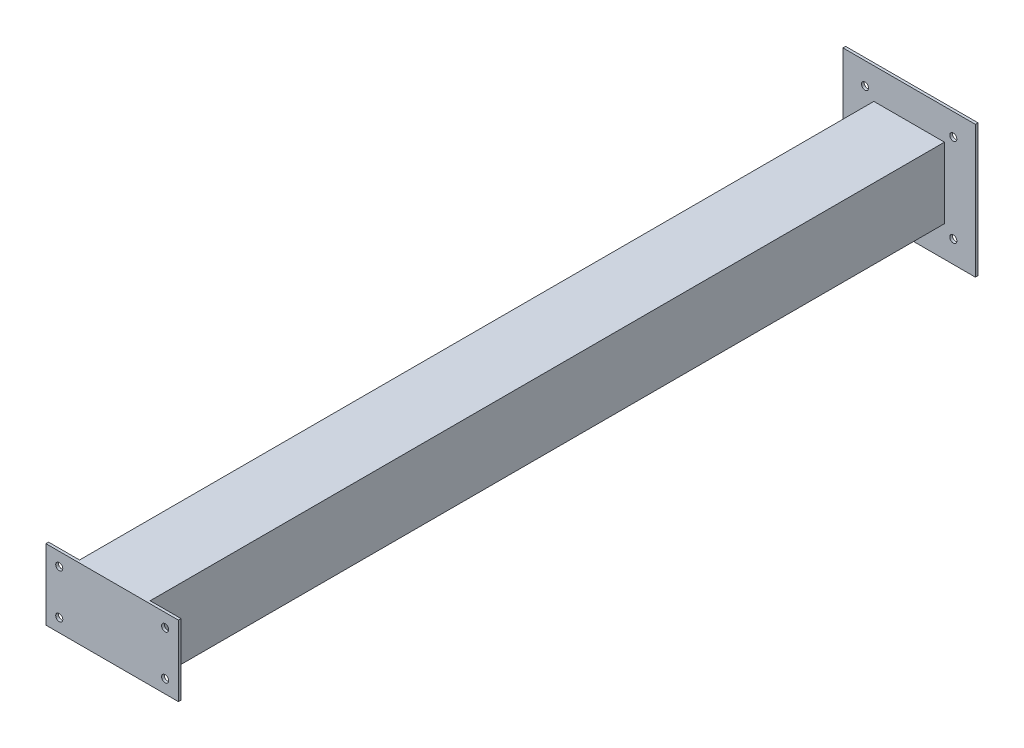
SolidWorks part; units mm, degrees
ref_plane "Front Plane" through (0, 0, 0) normal (0, 0, 1) x (1, 0, 0)
ref_plane "Top Plane" through (0, 0, 0) normal (0, 1, 0) x (1, 0, 0)
ref_plane "Right Plane" through (0, 0, 0) normal (1, 0, 0) x (0, 0, -1)
sketch "Sketch1" plane through (0, 0, 0) normal (0, 0, 1) x (1, 0, 0)
  line L1 (-40, 40) -> (40, 40)
  line L2 (-40, 40) -> (-40, -40)
  line L3 (-40, -40) -> (40, -40)
  line L4 (40, 40) -> (40, -40)
  line L5 (-40, 40) -> (40, -40) construction
  line L6 (-40, -40) -> (40, 40) construction
  point P0 (0, 0)
  dimension "D1" = 80
  dimension "D2" = 80
extrude "Boss-Extrude1" add sketch "Sketch1" along normal blind 900
shell "Shell1" thickness 3
sketch "Sketch2" plane through (0, 0, 0) normal (0, 0, -1) x (-1, 0, 0)
  line L0 (0, 75) -> (0, -75) construction
  line L1 (75, -75) -> (-75, -75)
  line L2 (75, -75) -> (75, 75)
  line L3 (75, 75) -> (-75, 75)
  line L4 (-75, -75) -> (-75, 75)
  line L5 (75, -75) -> (-75, 75) construction
  line L6 (75, 75) -> (-75, -75) construction
  line L7 (-75, 0) -> (75, 0) construction
  circle A0 centre (50, 50) radius 4
  circle A1 centre (-50, 50) radius 4
  circle A2 centre (50, -50) radius 4
  circle A3 centre (-50, -50) radius 4
  point P0 (0, 0)
  dimension "D5" = 8
  dimension "D1" = 100
  dimension "D2" = 100
  dimension "D3" = 150
  dimension "D4" = 150
extrude "Boss-Extrude2" add sketch "Sketch2" along normal blind 3
sketch "Sketch6" plane through (0, 0, 900) normal (0, 0, 1) x (1, 0, 0)
  line L0 (-75, -75) -> (-75, 75) construction
  line L1 (75, -40) -> (-75, -40)
  line L2 (75, -40) -> (75, 40)
  line L3 (75, 40) -> (-75, 40)
  line L4 (-75, -40) -> (-75, 40)
  line L5 (75, -40) -> (-75, 40) construction
  line L6 (75, 40) -> (-75, -40) construction
  point P0 (0, 0)
  dimension "D1" = 80
extrude "Boss-Extrude4" add sketch "Sketch6" along normal blind 3
sketch "Sketch7" plane through (0, 0, 903) normal (0, 0, 1) x (1, 0, 0)
  line L0 (0, 40) -> (0, 0) construction
  line L1 (75, 40) -> (-75, 40) construction
  line L2 (0, 0) -> (75, 0) construction
  line L3 (75, -40) -> (75, 40) construction
  circle A0 centre (-60, 25) radius 4
  circle A1 centre (60, 25) radius 4
  circle A2 centre (60, -25) radius 4
  circle A3 centre (-60, -25) radius 4
  dimension "D3" = 8
  dimension "D1" = 50
  dimension "D2" = 120
extrude "Cut-Extrude3" cut sketch "Sketch7" against normal up to next
sketch "Sketch10" plane through (0, 0, 0) normal (0, 1, 0) x (1, 0, 0)
  line L0 (-40, -900) -> (-75, -900)
  line L1 (-75, -900) -> (-40, -865)
  line L2 (-40, -900) -> (-40, 0) construction
  line L3 (-40, -865) -> (-40, -900)
  dimension "D1" = 35
extrude "Boss-Extrude5" add sketch "Sketch10" along normal mid plane 3
mirror "Mirror3" about plane through (0, 0, 0) normal (1, 0, 0) of "Boss-Extrude5"
